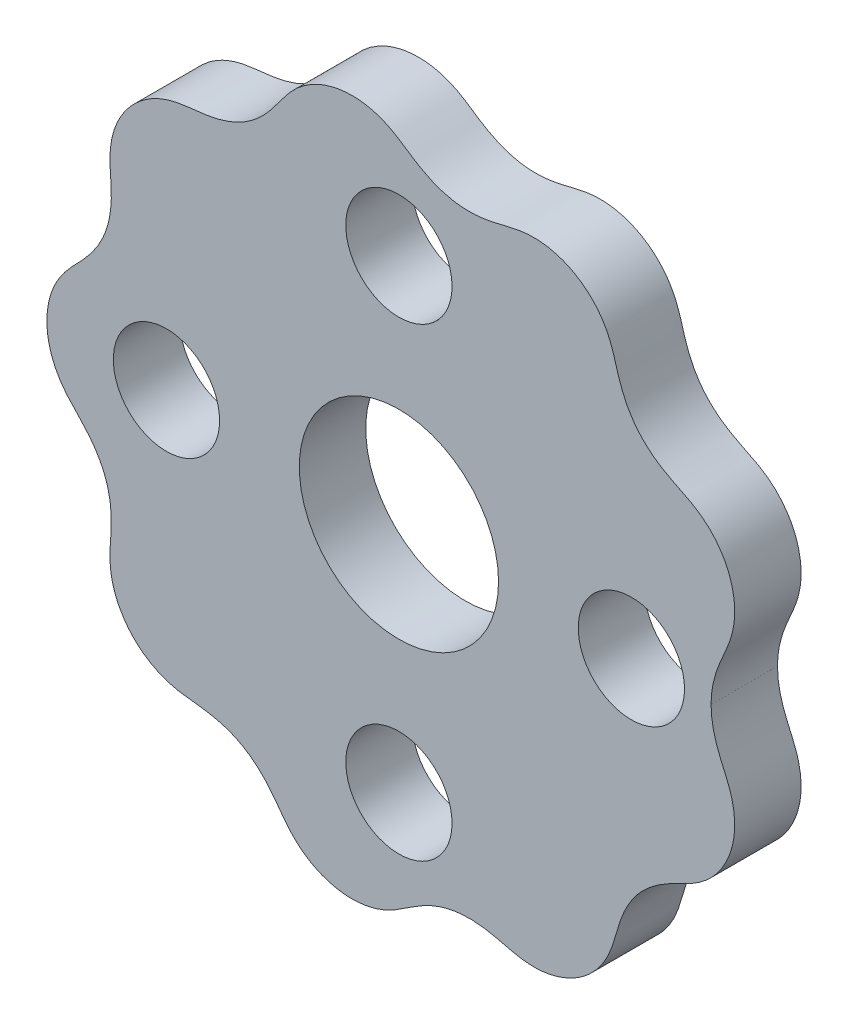
SolidWorks part; units mm, degrees
ref_plane "Front Plane" through (0, 0, 0) normal (0, 0, 1) x (1, 0, 0)
ref_plane "Top Plane" through (0, 0, 0) normal (0, 1, 0) x (1, 0, 0)
ref_plane "Right Plane" through (0, 0, 0) normal (1, 0, 0) x (0, 0, -1)
sketch "Sketch4" plane through (0, 0, 0) normal (0, 0, 1) x (1, 0, 0)
  spline S0 degree 4 poles (21.5253, 12.6675) (21.6797, 12.5896) (21.9864, 12.4298) (22.4361, 12.1698) (22.9982, 11.7645) (23.6024, 11.2171) (24.2032, 10.4954) (24.752, 9.5564) (25.1583, 8.3903) (25.3156, 7.2435) (25.2616, 6.1673) (25.0772, 5.3225) (24.8692, 4.7041) (24.6639, 4.2012) (24.4889, 3.8036) (24.2717, 3.317) (24.0668, 2.8306) (23.8878, 2.3392) (23.7416, 1.8425) (23.6577, 1.4899) (23.5998, 1.1848) (23.5615, 0.9289) (23.5368, 0.7231) (23.5182, 0.516) (23.5057, 0.3197) (23.5002, 0.0986) (23.4995, -0.0181) (23.5015, -0.1479) (23.5049, -0.264) (23.5111, -0.4041) (23.5219, -0.5619) (23.5393, -0.7476) (23.5658, -0.961) (23.6068, -1.2252) (23.6686, -1.5407) (23.7582, -1.9047) (23.8827, -2.3148) (24.0266, -2.7183) (24.1864, -3.1157) (24.3569, -3.5085) (24.5316, -3.8993) (24.7023, -4.2919) (24.9002, -4.7892) (25.0976, -5.401) (25.2717, -6.2487) (25.312, -7.3367) (25.13, -8.5234) (24.668, -9.7487) (24.0206, -10.7629) (23.2686, -11.558) (22.4774, -12.1547) (21.7037, -12.591) (20.9154, -12.9634) (20.1499, -13.3512) (19.253, -13.9006) (18.4446, -14.5666) (17.7509, -15.361) (17.1933, -16.259) (16.8298, -17.0333) (16.5469, -17.8352) (16.3173, -18.6484) (16.0831, -19.4562) (15.7759, -20.2365) (15.3148, -21.0705) (14.6531, -21.9103) (13.7597, -22.6898) (12.6261, -23.3256) (11.4829, -23.6849) (10.3957, -23.8107) (9.4061, -23.7593) (8.5329, -23.5962) (7.6897, -23.3747) (6.854, -23.1797) (5.8138, -23.024) (4.7665, -23.0146) (3.7244, -23.1772) (2.72, -23.5067) (1.9439, -23.8661) (1.2116, -24.2985) (0.513, -24.774) (-0.1856, -25.2422) (-0.9225, -25.6425) (-1.8118, -25.985) (-2.8585, -26.203) (-4.0439, -26.226) (-5.321, -25.9844) (-6.4277, -25.5249) (-7.3414, -24.9225) (-8.0665, -24.247) (-8.6306, -23.5608) (-9.1342, -22.8492) (-9.649, -22.1626) (-10.3457, -21.3747) (-11.1419, -20.6942) (-12.0447, -20.1489) (-13.0259, -19.7556) (-13.8515, -19.5321) (-14.6903, -19.3926) (-15.5311, -19.3078) (-16.3673, -19.2174) (-17.189, -19.0504) (-18.0905, -18.7412) (-19.0325, -18.2355) (-19.9554, -17.4911) (-20.7784, -16.4852) (-21.3309, -15.4218) (-21.6437, -14.373) (-21.7649, -13.3895) (-21.756, -12.5013) (-21.6844, -11.6324) (-21.6374, -10.7756) (-21.6646, -9.7241) (-21.8371, -8.691) (-22.1782, -7.693) (-22.6769, -6.7611) (-23.1656, -6.0591) (-23.7186, -5.413) (-24.3081, -4.8076) (-24.8906, -4.2009) (-25.4128, -3.5448) (-25.9046, -2.7285) (-26.3012, -1.7356) (-26.5297, -0.5721) (-26.5137, 0.7274) (-26.2535, 1.8972) (-25.8189, 2.9017) (-25.2797, 3.7331) (-24.7019, 4.4078) (-24.0885, 5.0273) (-23.5018, 5.6535) (-22.8468, 6.4764) (-22.3148, 7.3787) (-21.9345, 8.3624) (-21.7175, 9.3969) (-21.6406, 10.2488) (-21.6489, 11.0991) (-21.7113, 11.9418) (-21.7676, 12.781) (-21.7459, 13.6193) (-21.598, 14.5608) (-21.2636, 15.5762) (-20.6909, 16.6145) (-19.8433, 17.5997) (-18.8921, 18.3286) (-17.9135, 18.8188) (-16.9661, 19.1091) (-16.0898, 19.2546) (-15.2217, 19.3349) (-14.3697, 19.4374) (-13.3389, 19.6468) (-12.3515, 19.9959) (-11.4278, 20.505) (-10.5966, 21.158) (-9.9901, 21.7611) (-9.4498, 22.4178) (-8.9559, 23.1035) (-8.4596, 23.7825) (-7.9042, 24.4108) (-7.1858, 25.0369) (-6.2769, 25.5999) (-5.1708, 26.0272) (-3.8882, 26.2372) (-2.691, 26.1841) (-1.6263, 25.9307) (-0.7139, 25.5441) (0.0509, 25.0924) (0.7675, 24.5959) (1.4861, 24.1268) (2.4102, 23.6245) (3.3911, 23.2572) (4.4259, 23.0534) (5.4824, 23.0193) (6.3347, 23.0915) (7.1706, 23.2472) (7.9897, 23.455) (8.8064, 23.6562) (9.6357, 23.7804) (10.5885, 23.7984) (11.6467, 23.6455) (12.7686, 23.2619) (13.8862, 22.5983) (14.7692, 21.7882) (15.4219, 20.9097) (15.8724, 20.0271) (16.168, 19.1894) (16.3978, 18.3484) (16.6467, 17.5272) (17.0318, 16.5484) (17.547, 15.6366) (18.2087, 14.8152) (18.9961, 14.11) (19.6953, 13.6174) (20.4358, 13.1993) (21.1968, 12.832) (21.9517, 12.4612) (22.6669, 12.0233) (23.4084, 11.4246) (24.1207, 10.6274) (24.7325, 9.6142) (25.1613, 8.3919) (25.3171, 7.215) (25.2638, 6.2479) (25.1175, 5.5104) (24.967, 4.9942) (24.8225, 4.5891) (24.6799, 4.2408) (24.5297, 3.8959) (24.3986, 3.6014) (24.2703, 3.3101) (24.1274, 2.971) (23.9946, 2.6323) (23.8591, 2.2416) (23.7423, 1.845) (23.6463, 1.4427) (23.5821, 1.0866) (23.5419, 0.7791) (23.5185, 0.5208) (23.506, 0.3245) (23.5003, 0.105) (23.4995, -0.0107) (23.5013, -0.1369) (23.5043, -0.2489) (23.5101, -0.385) (23.5201, -0.5382) (23.5362, -0.7171) (23.5607, -0.9237) (23.5913, -1.1282) (23.6277, -1.332) (23.6804, -1.5854) (23.7548, -1.887) (23.8569, -2.2347) (23.9923, -2.6261) (24.1451, -3.0165) (24.3118, -3.4067) (24.4867, -3.7988) (24.6619, -4.1964) (24.8263, -4.5987) (24.9717, -5.0083) (25.1225, -5.5304) (25.2665, -6.2712) (25.3158, -7.2384) (25.1595, -8.3854) (24.7541, -9.5519) (24.2059, -10.4915) (23.6055, -11.2138) (23.0017, -11.7617) (22.4397, -12.1674) (21.9901, -12.4277) (21.6834, -12.5877) (21.529, -12.6657) knots 0 0 0 0 0 0.003494 0.006987 0.010481 0.013975 0.01993 0.025885 0.032325 0.038764 0.043153 0.047542 0.049736 0.051931 0.054125 0.05632 0.060502 0.062593 0.064684 0.066775 0.067821 0.068867 0.069912 0.070958 0.072003 0.073049 0.07359 0.074131 0.074671 0.075212 0.076294 0.077376 0.078457 0.079539 0.081702 0.083866 0.086029 0.088193 0.090356 0.092518 0.09468 0.096842 0.099005 0.103329 0.107653 0.114269 0.120885 0.127405 0.133924 0.138402 0.142879 0.147357 0.151834 0.15602 0.160206 0.168578 0.17289 0.177201 0.181513 0.185824 0.190049 0.194275 0.198501 0.202726 0.209245 0.215764 0.222284 0.228803 0.23328 0.237758 0.242236 0.246713 0.250899 0.255085 0.263457 0.267769 0.27208 0.276392 0.280703 0.284928 0.289154 0.29338 0.297605 0.304124 0.310643 0.317163 0.323682 0.328159 0.332637 0.337115 0.341592 0.345778 0.349964 0.358336 0.362648 0.366959 0.371271 0.375582 0.379807 0.384033 0.388258 0.392484 0.399003 0.405522 0.412042 0.418561 0.423038 0.427516 0.431994 0.436471 0.440657 0.444843 0.453215 0.457527 0.461838 0.466149 0.470461 0.474686 0.478912 0.483137 0.487363 0.493882 0.500401 0.506921 0.51344 0.517917 0.522395 0.526873 0.53135 0.535536 0.539722 0.548094 0.552406 0.556717 0.561028 0.56534 0.569565 0.573791 0.578016 0.582242 0.588761 0.59528 0.601799 0.608319 0.612796 0.617274 0.621751 0.626229 0.630415 0.634601 0.642973 0.647285 0.651596 0.655907 0.660219 0.664444 0.66867 0.672895 0.677121 0.68364 0.690159 0.696678 0.703198 0.707675 0.712153 0.71663 0.721108 0.725294 0.72948 0.737852 0.742164 0.746475 0.750786 0.755098 0.759323 0.763549 0.767774 0.772 0.778519 0.785038 0.791557 0.798077 0.802554 0.807032 0.811509 0.815987 0.820173 0.824359 0.832731 0.837043 0.841354 0.845665 0.849977 0.854202 0.858428 0.862653 0.866879 0.873398 0.879917 0.886393 0.892869 0.897212 0.899384 0.901555 0.903727 0.905898 0.906984 0.909156 0.910242 0.912329 0.914417 0.916505 0.918593 0.920681 0.922769 0.923813 0.924856 0.9259 0.926944 0.927467 0.92799 0.928513 0.929036 0.930081 0.931127 0.932172 0.933218 0.934264 0.935309 0.937401 0.939492 0.941583 0.943674 0.945869 0.948063 0.950258 0.952453 0.954647 0.956842 0.961231 0.967671 0.974111 0.980067 0.986023 0.989517 0.993011 0.996506 1 1 1 1 1 construction
  spline S1 degree 4 poles (23.5, 0) (23.5, -0.0229) (23.5003, -0.069) (23.5015, -0.1479) (23.5049, -0.264) (23.5111, -0.4041) (23.5219, -0.5619) (23.5393, -0.7476) (23.5658, -0.961) (23.6068, -1.2252) (23.6686, -1.5407) (23.7582, -1.9047) (23.8827, -2.3148) (24.0266, -2.7183) (24.1864, -3.1157) (24.3569, -3.5085) (24.5316, -3.8993) (24.7023, -4.2919) (24.9002, -4.7892) (25.0976, -5.401) (25.2717, -6.2487) (25.312, -7.3367) (25.13, -8.5234) (24.668, -9.7487) (24.0206, -10.7629) (23.2686, -11.558) (22.4774, -12.1547) (21.7037, -12.591) (20.9154, -12.9634) (20.1499, -13.3512) (19.253, -13.9006) (18.4446, -14.5666) (17.7509, -15.361) (17.1933, -16.259) (16.8298, -17.0333) (16.5469, -17.8352) (16.3173, -18.6484) (16.0831, -19.4562) (15.7759, -20.2365) (15.3148, -21.0705) (14.6531, -21.9103) (13.7597, -22.6898) (12.6261, -23.3256) (11.4829, -23.6849) (10.3957, -23.8107) (9.4061, -23.7593) (8.5329, -23.5962) (7.6897, -23.3747) (6.854, -23.1797) (5.8138, -23.024) (4.7665, -23.0146) (3.7244, -23.1772) (2.72, -23.5067) (1.9439, -23.8661) (1.2116, -24.2985) (0.513, -24.774) (-0.1856, -25.2422) (-0.9225, -25.6425) (-1.8118, -25.985) (-2.8585, -26.203) (-4.0439, -26.226) (-5.321, -25.9844) (-6.4277, -25.5249) (-7.3414, -24.9225) (-8.0665, -24.247) (-8.6306, -23.5608) (-9.1342, -22.8492) (-9.649, -22.1626) (-10.3457, -21.3747) (-11.1419, -20.6942) (-12.0447, -20.1489) (-13.0259, -19.7556) (-13.8515, -19.5321) (-14.6903, -19.3926) (-15.5311, -19.3078) (-16.3673, -19.2174) (-17.189, -19.0504) (-18.0905, -18.7412) (-19.0325, -18.2355) (-19.9554, -17.4911) (-20.7784, -16.4852) (-21.3309, -15.4218) (-21.6437, -14.373) (-21.7649, -13.3895) (-21.756, -12.5013) (-21.6844, -11.6324) (-21.6374, -10.7756) (-21.6646, -9.7241) (-21.8371, -8.691) (-22.1782, -7.693) (-22.6769, -6.7611) (-23.1656, -6.0591) (-23.7186, -5.413) (-24.3081, -4.8076) (-24.8906, -4.2009) (-25.4128, -3.5448) (-25.9046, -2.7285) (-26.3012, -1.7356) (-26.5297, -0.5721) (-26.5137, 0.7274) (-26.2535, 1.8972) (-25.8189, 2.9017) (-25.2797, 3.7331) (-24.7019, 4.4078) (-24.0885, 5.0273) (-23.5018, 5.6535) (-22.8468, 6.4764) (-22.3148, 7.3787) (-21.9345, 8.3624) (-21.7175, 9.3969) (-21.6406, 10.2488) (-21.6489, 11.0991) (-21.7113, 11.9418) (-21.7676, 12.781) (-21.7459, 13.6193) (-21.598, 14.5608) (-21.2636, 15.5762) (-20.6909, 16.6145) (-19.8433, 17.5997) (-18.8921, 18.3286) (-17.9135, 18.8188) (-16.9661, 19.1091) (-16.0898, 19.2546) (-15.2217, 19.3349) (-14.3697, 19.4374) (-13.3389, 19.6468) (-12.3515, 19.9959) (-11.4278, 20.505) (-10.5966, 21.158) (-9.9901, 21.7611) (-9.4498, 22.4178) (-8.9559, 23.1035) (-8.4596, 23.7825) (-7.9042, 24.4108) (-7.1858, 25.0369) (-6.2769, 25.5999) (-5.1708, 26.0272) (-3.8882, 26.2372) (-2.691, 26.1841) (-1.6263, 25.9307) (-0.7139, 25.5441) (0.0509, 25.0924) (0.7675, 24.5959) (1.4861, 24.1268) (2.4102, 23.6245) (3.3911, 23.2572) (4.4259, 23.0534) (5.4824, 23.0193) (6.3347, 23.0915) (7.1706, 23.2472) (7.9897, 23.455) (8.8064, 23.6562) (9.6357, 23.7804) (10.5885, 23.7984) (11.6467, 23.6455) (12.7686, 23.2619) (13.8862, 22.5983) (14.7692, 21.7882) (15.4219, 20.9097) (15.8724, 20.0271) (16.168, 19.1894) (16.3978, 18.3484) (16.6467, 17.5272) (17.0318, 16.5484) (17.547, 15.6366) (18.2087, 14.8152) (18.9961, 14.11) (19.6953, 13.6174) (20.4358, 13.1993) (21.1968, 12.832) (21.9517, 12.4612) (22.6669, 12.0233) (23.4084, 11.4246) (24.1207, 10.6274) (24.7325, 9.6142) (25.1613, 8.3919) (25.3171, 7.215) (25.2638, 6.2479) (25.1175, 5.5104) (24.967, 4.9942) (24.8225, 4.5891) (24.6799, 4.2408) (24.5297, 3.8959) (24.3986, 3.6014) (24.2703, 3.3101) (24.1274, 2.971) (23.9946, 2.6323) (23.8591, 2.2416) (23.7423, 1.845) (23.6463, 1.4427) (23.5821, 1.0866) (23.5419, 0.7791) (23.5185, 0.5208) (23.506, 0.3245) (23.5011, 0.1364) (23.5, 0.0496) (23.5, 0.0055) knots 0.073049 0.073049 0.073049 0.073049 0.073049 0.07359 0.074131 0.074671 0.075212 0.076294 0.077376 0.078457 0.079539 0.081702 0.083866 0.086029 0.088193 0.090356 0.092518 0.09468 0.096842 0.099005 0.103329 0.107653 0.114269 0.120885 0.127405 0.133924 0.138402 0.142879 0.147357 0.151834 0.15602 0.160206 0.168578 0.17289 0.177201 0.181513 0.185824 0.190049 0.194275 0.198501 0.202726 0.209245 0.215764 0.222284 0.228803 0.23328 0.237758 0.242236 0.246713 0.250899 0.255085 0.263457 0.267769 0.27208 0.276392 0.280703 0.284928 0.289154 0.29338 0.297605 0.304124 0.310643 0.317163 0.323682 0.328159 0.332637 0.337115 0.341592 0.345778 0.349964 0.358336 0.362648 0.366959 0.371271 0.375582 0.379807 0.384033 0.388258 0.392484 0.399003 0.405522 0.412042 0.418561 0.423038 0.427516 0.431994 0.436471 0.440657 0.444843 0.453215 0.457527 0.461838 0.466149 0.470461 0.474686 0.478912 0.483137 0.487363 0.493882 0.500401 0.506921 0.51344 0.517917 0.522395 0.526873 0.53135 0.535536 0.539722 0.548094 0.552406 0.556717 0.561028 0.56534 0.569565 0.573791 0.578016 0.582242 0.588761 0.59528 0.601799 0.608319 0.612796 0.617274 0.621751 0.626229 0.630415 0.634601 0.642973 0.647285 0.651596 0.655907 0.660219 0.664444 0.66867 0.672895 0.677121 0.68364 0.690159 0.696678 0.703198 0.707675 0.712153 0.71663 0.721108 0.725294 0.72948 0.737852 0.742164 0.746475 0.750786 0.755098 0.759323 0.763549 0.767774 0.772 0.778519 0.785038 0.791557 0.798077 0.802554 0.807032 0.811509 0.815987 0.820173 0.824359 0.832731 0.837043 0.841354 0.845665 0.849977 0.854202 0.858428 0.862653 0.866879 0.873398 0.879917 0.886393 0.892869 0.897212 0.899384 0.901555 0.903727 0.905898 0.906984 0.909156 0.910242 0.912329 0.914417 0.916505 0.918593 0.920681 0.922769 0.923813 0.924856 0.9259 0.926944 0.926944 0.926944 0.926944 0.926944
  spline S2 degree 2 poles (23.5, 0) (23.5, 0.0081) (23.5, 0.0161) knots 0 0 0 1 1 1
extrude "Boss-Extrude2" add sketch "Sketch4" along normal blind 5 contours S1 S2
sketch "Sketch5" plane through (0, 0, 5) normal (0, 0, 1) x (1, 0, 0)
  circle A0 centre (0, 0) radius 7.5
extrude "Cut-Extrude1" cut sketch "Sketch5" against normal blind 10
sketch "Sketch6" plane through (0, 0, 5) normal (0, 0, 1) x (1, 0, 0)
  circle A0 centre (0, 0) radius 17.5
  circle A1 centre (0, 17.5) radius 4
  circle A2 centre (17.5, 0) radius 4
  circle A3 centre (0, -17.5) radius 4
  circle A4 centre (-17.5, 0) radius 4
  point P14 (0, 0)
  dimension "D1" = 35
  dimension "D2" = 8
  dimension "D3" = 4
extrude "Cut-Extrude2" cut sketch "Sketch6" against normal blind 10 contours A0 A1 | A0 A1 | A0 A2 | A0 A2 | A0 A3 | A0 A3 | A0 A4 | A0 A4
